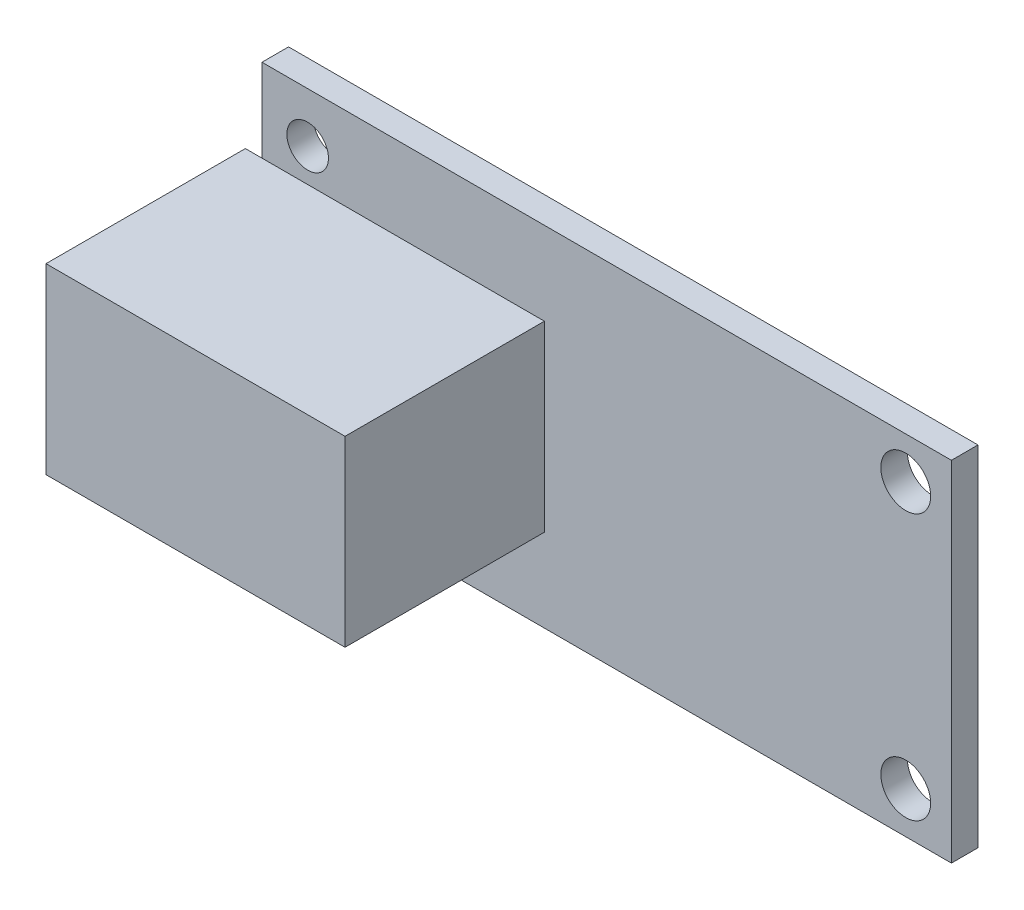
SolidWorks part; units mm, degrees
ref_plane "Front" through (0, 0, 0) normal (0, 0, 1) x (1, 0, 0)
ref_plane "Top" through (0, 0, 0) normal (0, 1, 0) x (1, 0, 0)
ref_plane "Right" through (0, 0, 0) normal (1, 0, 0) x (0, 0, -1)
sketch "Эскиз1" plane through (0, 0, 0) normal (0, 0, 1) x (1, 0, 0)
  line L1 (-20.75, 10.5) -> (20.75, 10.5)
  line L2 (-20.75, 10.5) -> (-20.75, -10.5)
  line L3 (-20.75, -10.5) -> (20.75, -10.5)
  line L4 (20.75, 10.5) -> (20.75, -10.5)
  point P4 (0, -10.5)
  point P5 (20.75, 0)
  dimension "D1" = 21
  dimension "D2" = 41.5
extrude "Плата" add sketch "Эскиз1" along normal blind 1.6
sketch "Эскиз2" plane through (0, 0, 1.6) normal (0, 0, 1) x (1, 0, 0)
  line L0 (-20.75, 10.5) -> (-20.75, -10.5) construction
  line L1 (-21.75, 5.5) -> (-3.75, 5.5)
  line L2 (-21.75, 5.5) -> (-21.75, -5.5)
  line L3 (-21.75, -5.5) -> (-3.75, -5.5)
  line L4 (-3.75, 5.5) -> (-3.75, -5.5)
  point P6 (-21.75, 0)
  dimension "D1" = 11
  dimension "D2" = 18
  dimension "D3" = 1
extrude "RJ-9" add sketch "Эскиз2" along normal blind 12
sketch "Эскиз3" plane through (0, 0, 1.6) normal (0, 0, 1) x (1, 0, 0)
  line L0 (0, 0) -> (20.75, 0) construction
  line L2 (0, 10.5) -> (0, 0) construction
  line L3 (20.75, 10.5) -> (-20.75, 10.5) construction
  line L4 (20.75, -10.5) -> (20.75, 10.5) construction
  line L5 (-18, 7.5) -> (-18, 8) construction
  circle A0 centre (-18, 7.5) radius 1.25
  circle A1 centre (18, 8) radius 1.5
  circle A2 centre (18, -8) radius 1.5
  circle A3 centre (-18, -7.5) radius 1.25
  dimension "D1" = 18
  dimension "D2" = 36
  dimension "D3" = 8
  dimension "D4" = 3
  dimension "D5" = 2.5
  dimension "D6" = 7.5
extrude "Крепежные отверстия" cut sketch "Эскиз3" against normal through all
